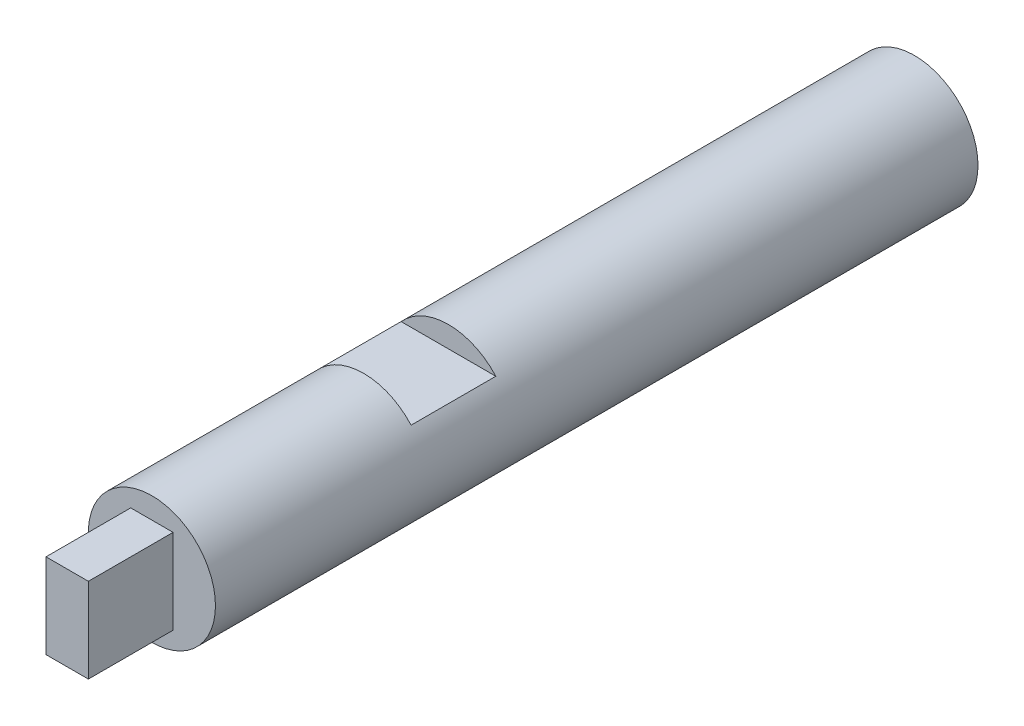
SolidWorks part; units mm, degrees
ref_plane "Front Plane" through (0, 0, 0) normal (0, 0, 1) x (1, 0, 0)
ref_plane "Top Plane" through (0, 0, 0) normal (0, 1, 0) x (1, 0, 0)
ref_plane "Right Plane" through (0, 0, 0) normal (1, 0, 0) x (0, 0, -1)
sketch "Sketch1" plane through (0, 0, 0) normal (0, 0, 1) x (1, 0, 0)
  circle A0 centre (-50, 6) radius 1.5
extrude "Boss-Extrude1" add sketch "Sketch1" along normal up to surface (18 mm away)
sketch "Sketch2" plane through (0, 0, 18) normal (0, 0, 1) x (1, 0, 0)
  line L1 (-50.5, 5) -> (-49.5, 5)
  line L2 (-50.5, 5) -> (-50.5, 7)
  line L3 (-50.5, 7) -> (-49.5, 7)
  line L4 (-49.5, 5) -> (-49.5, 7)
  line L5 (-50.5, 5) -> (-49.5, 7) construction
  line L6 (-50.5, 7) -> (-49.5, 5) construction
  point P0 (-50, 6)
extrude "Boss-Extrude2" add sketch "Sketch2" along normal blind 2
sketch "Sketch3" plane through (0, 0, 18) normal (0, 0, 1) x (1, 0, 0)
  line L0 (-48.882, 7) -> (-51.118, 7)
  line L1 (-51.118, 7) -> (-51.118, 8)
  line L2 (-51.118, 8) -> (-48.882, 8)
  line L3 (-48.882, 8) -> (-48.882, 7)
  line L4 (-50, 7) -> (-50, 7.5) construction
  circle A0 centre (-50, 6) radius 1.5 construction
  dimension "D1" = 0.5
  dimension "D2" = 1
extrude "Cut-Extrude1" cut sketch "Sketch3" against normal blind 2 from offset 5
